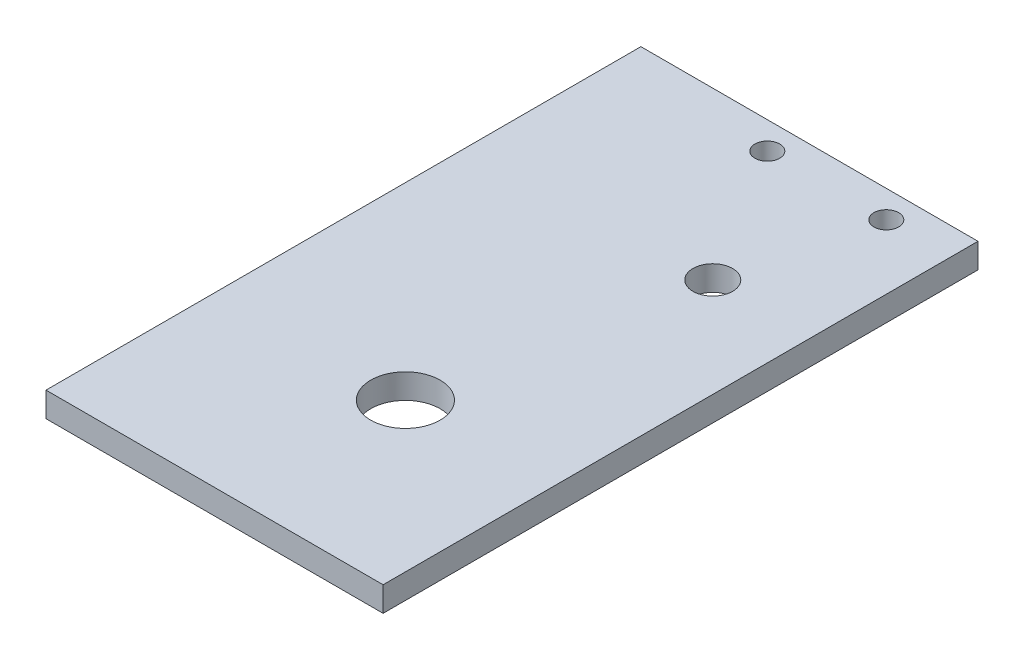
SolidWorks part; units mm, degrees
ref_plane "Plan de face" through (0, 0, 0) normal (0, 0, 1) x (1, 0, 0)
ref_plane "Plan de dessus" through (0, 0, 0) normal (0, 1, 0) x (1, 0, 0)
ref_plane "Plan de droite" through (0, 0, 0) normal (1, 0, 0) x (0, 0, -1)
sketch "Esquisse1" plane through (0, 0, 0) normal (0, 0, 1) x (1, 0, 0)
  line L0 (0, 0) -> (0, -40)
  line L1 (0, -40) -> (-68, -40)
  line L5 (-68, -35) -> (-5, -35)
  line L6 (-5, -35) -> (-5, 0)
  line L7 (-5, 0) -> (0, 0)
  line L8 (-68, -35) -> (-68, -40)
  dimension "D1" = 5
  dimension "D2" = 40
  dimension "D3" = 5
  dimension "D4" = 68
extrude "Boss.-Extru.1" add sketch "Esquisse1" along normal blind 120
sketch "Esquisse2" plane through (-5, 0, 0) normal (-1, 0, 0) x (0, 0, 1)
  line L0 (120, -35) -> (0, -35) construction
  line L1 (0, 0) -> (45, 0)
  line L2 (0, 0) -> (0, -35)
  line L3 (0, -35) -> (45, -35)
  line L4 (45, 0) -> (45, -35)
  line L7 (120, 0) -> (75, 0)
  line L8 (120, 0) -> (120, -35)
  line L9 (120, -35) -> (75, -35)
  line L10 (75, 0) -> (75, -35)
  dimension "D1" = 30
extrude "Enlèv. mat.-Extru.1" cut sketch "Esquisse2" against normal blind 10
sketch "Esquisse3" plane through (0, -40, 0) normal (0, -1, 0) x (1, 0, 0)
  line L0 (0, 75) -> (0, 120) construction
  line L1 (-68, 120) -> (0, 120) construction
  circle A0 centre (-30, 85.5) radius 7
  dimension "D1" = 14
  dimension "D2" = 30
  dimension "D3" = 34.5
extrude "Enlèv. mat.-Extru.2" cut sketch "Esquisse3" against normal blind 10
sketch "Esquisse4" plane through (-5, 0, 0) normal (-1, 0, 0) x (0, 0, 1)
  line L0 (75, 0) -> (45, 0) construction
  circle A0 centre (50, -5) radius 3
  circle A1 centre (50, -25) radius 3
  dimension "D1" = 6
  dimension "D2" = 20
  dimension "D3" = 5
extrude "Enlèv. mat.-Extru.3" cut sketch "Esquisse4" against normal through all
sketch "Esquisse5" plane through (0, -40, 0) normal (0, -1, 0) x (-1, 0, 0)
  circle A0 centre (37, -5.5) radius 3
  circle A1 centre (13, -5.5) radius 3
  circle A2 centre (30, -85.5) radius 7 construction
  dimension "D1" = 80
  dimension "D2" = 80
hole_wizard "Trou taraudé M61" positions "Esquisse3D1" profile "Esquisse6" tap size "M6" standard "ISO"
sketch3d "Esquisse3D1"
  point P0 (-37, -40, 5.5)
  point P3 (-13, -40, 5.5)
sketch "Esquisse6" plane through (-37, -40, 5.5) normal (1, 0, 0) x (0, 0, -1)
  line L0 (0, 0) -> (0, 16.5022)
  line L1 (0, 16.5022) -> (2.5, 15)
  line L2 (2.5, 15) -> (2.5, 0)
  line L5 (2.5, 0) -> (0, 0)
  line L10 (0, 16.5022) -> (-2.5, 15) construction
  line L11 (0, -6.35) -> (0, 107.95) construction
  dimension "Diamètre du trou pour taraudage" = 5
  dimension "Profondeur du trou pour taraudage" = 15
  dimension "Angle de pointe" = 118
cosmetic thread "Filetage de perçage1" parameters "D1"=5, "D2"=6
cosmetic thread "Filetage de perçage2" parameters "D1"=5, "D2"=6
sketch "Esquisse7" plane through (-5, 0, 0) normal (-1, 0, 0) x (0, 0, 1)
  line L1 (45, -35) -> (75, -35)
  line L2 (45, -35) -> (45, 0)
  line L3 (45, 0) -> (75, 0)
  line L4 (75, -35) -> (75, 0)
extrude "Enlèv. mat.-Extru.4" cut sketch "Esquisse7" against normal blind 10
sketch "Esquisse8" plane through (0, -35, 0) normal (0, 1, 0) x (1, 0, 0)
  line L0 (0, 0) -> (0, -120) construction
  line L1 (0, 0) -> (-68, 0) construction
  circle A0 centre (-20, -33.5) radius 4
  dimension "D1" = 20
  dimension "D2" = 33.5
  dimension "D3" = 8
extrude "Enlèv. mat.-Extru.5" cut sketch "Esquisse8" against normal blind 20
